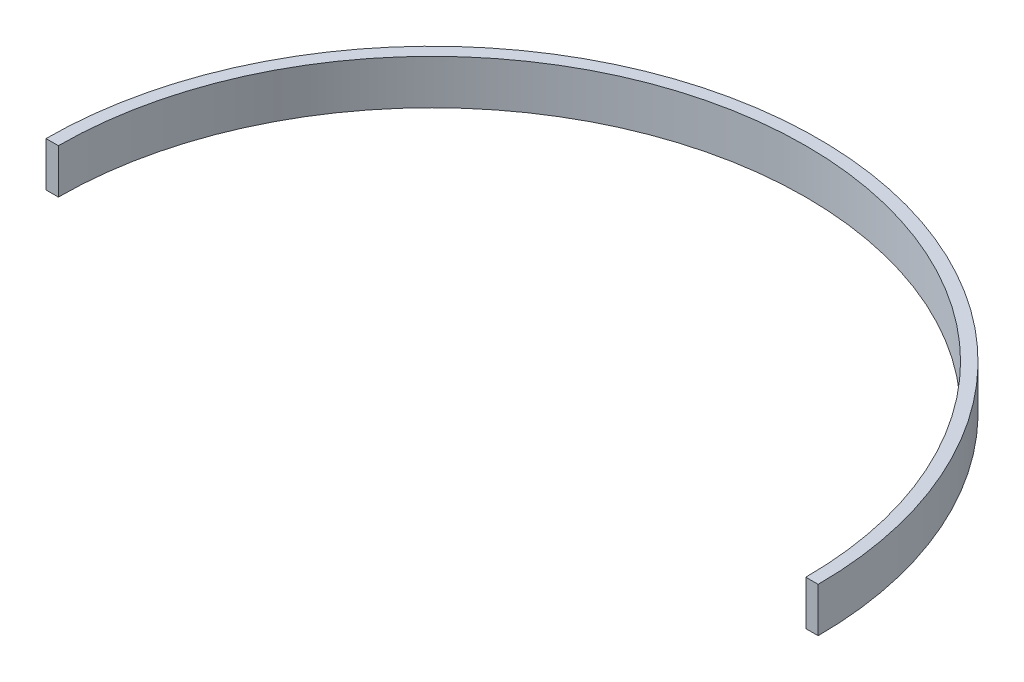
SolidWorks part; units mm, degrees
ref_plane "Front Plane" through (0, 0, 0) normal (0, 0, 1) x (1, 0, 0)
ref_plane "Top Plane" through (0, 0, 0) normal (0, 1, 0) x (1, 0, 0)
ref_plane "Right Plane" through (0, 0, 0) normal (1, 0, 0) x (0, 0, -1)
sketch "Sketch2" plane through (0, 0, 0) normal (0, 1, 0) x (1, 0, 0)
  line L0 (0, 0) -> (0, 45) construction
  line L1 (-75.5, 0) -> (-78, 0)
  line L2 (75.5, 0) -> (78, 0)
  line L3 (-82.5, 0) -> (-99.6521, 0) construction
  line L4 (0, 0) -> (-75.5, 0) construction
  line L5 (0, 0) -> (75.5, 0) construction
  line L6 (82.5, 0) -> (99.6521, 0) construction
  line L7 (-78, 0) -> (-82.5, 0) construction
  line L8 (78, 0) -> (82.5, 0) construction
  arc A0 (82.5, 0) -> (-82.5, 0) centre (0, 0) ccw construction
  arc A2 (75.5, 0) -> (-75.5, 0) centre (0, 0) ccw
  arc A3 (-82.5, 0) -> (82.5, 0) centre (0, 0) ccw construction
  circle A4 centre (0, 0) radius 82.5 construction
  arc A5 (-75.5, 0) -> (75.5, 0) centre (0, 0) ccw construction
  circle A6 centre (0, 0) radius 75.5 construction
  arc A7 (78, 0) -> (-78, 0) centre (0, 0) ccw
  dimension "D1" = 165
  dimension "D2" = 7
  dimension "D3" = 90
  dimension "D4" = 2.5
extrude "Boss-Extrude1" add sketch "Sketch2" along normal mid plane 9
